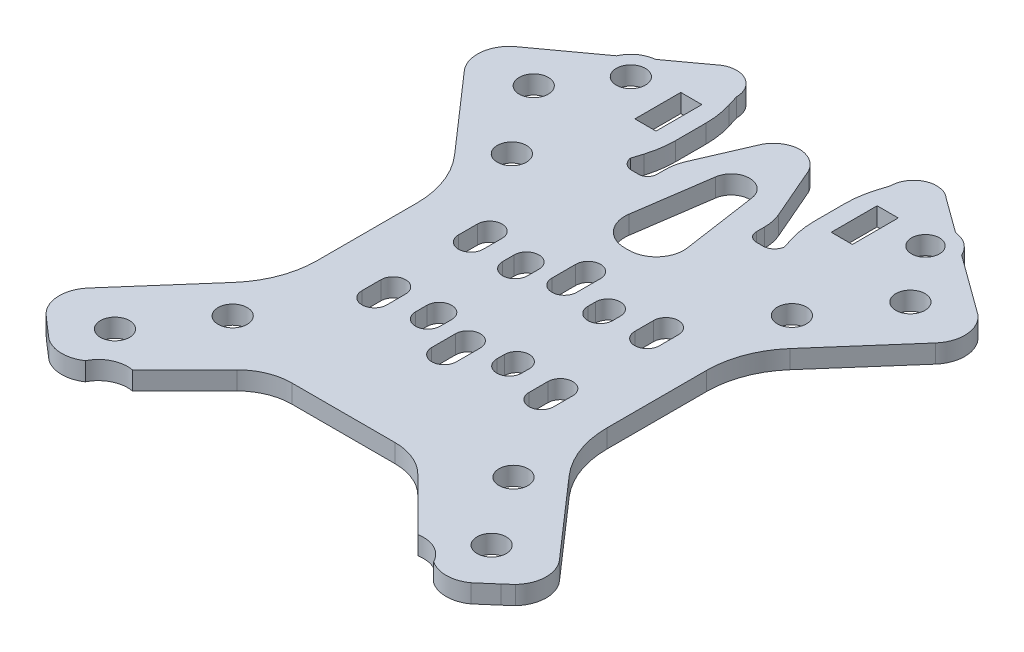
SolidWorks part; units mm, degrees
ref_plane "Alzado" through (0, 0, 0) normal (0, 0, 1) x (1, 0, 0)
ref_plane "Planta" through (0, 0, 0) normal (0, 1, 0) x (1, 0, 0)
ref_plane "Vista lateral" through (0, 0, 0) normal (1, 0, 0) x (0, 0, -1)
sketch "Croquis2" plane through (0, 0, 0) normal (0, 1, 0) x (1, 0, 0)
  line L0 (0, -1035.6845) -> (0, -17.8422) construction
  line L5 (0.7327, 0.4652) -> (1.362, 0.4652) construction
  line L7 (-18.2554, -12.0161) -> (-25.6541, -20.4709)
  line L14 (-15.7808, 5.4307) -> (-15.7808, -5.4307)
  line L18 (0, -8.7278) -> (0, 9.8136) construction
  line L20 (-24.7424, -25.9141) -> (-22.9722, -27.4461)
  line L25 (15.4321, 26.7753) -> (15.4536, 26.7998)
  line L29 (0, 8.3081) -> (0, 5.7183) construction
  line L30 (-18.2554, 12.0161) -> (-25.6541, 20.4709)
  line L31 (-24.7424, -25.9141) -> (-25.5735, -25.1696)
  line L45 (-1.35, 8.3081) -> (-1.35, 5.7183)
  line L53 (-9.1589, -5.8146) -> (-9.1589, -3.7612) construction
  line L54 (-7.8089, -5.8146) -> (-7.8089, -3.7612)
  line L55 (-10.5089, -5.8146) -> (-10.5089, -3.7612)
  line L58 (-4.2409, -4.9118) -> (-4.2409, -3.6663) construction
  line L59 (-2.8909, -4.9118) -> (-2.8909, -3.6663)
  line L60 (-5.5909, -4.9118) -> (-5.5909, -3.6663)
  line L61 (1.35, 8.3081) -> (1.35, 5.7183)
  line L64 (4.6229, 5.8422) -> (4.6229, 5.0048) construction
  line L67 (9.5409, -6.317) -> (9.5409, -4.2636) construction
  line L68 (8.1909, -6.317) -> (8.1909, -4.2636)
  line L69 (10.8909, -6.317) -> (10.8909, -4.2636)
  line L70 (4.6229, -4.9118) -> (4.6229, -4.0745) construction
  line L71 (3.2729, -4.9118) -> (3.2729, -4.0745)
  line L72 (5.9729, -4.9118) -> (5.9729, -4.0745)
  line L74 (-11.8441, 30.2416) -> (-9.5441, 30.2416)
  line L81 (-15.5416, -25.7927) -> (-9.8561, -20.0974)
  line L82 (5.6203, -18.3469) -> (-5.6203, -18.3469)
  line L94 (0, -7.3778) -> (0, -4.7879) construction
  line L95 (-1.35, -7.3778) -> (-1.35, -4.7879)
  line L96 (1.35, -7.3778) -> (1.35, -4.7879)
  line L103 (0.2351, 12.5224) -> (-0.2351, 12.5224)
  line L104 (-3.1825, 15.9307) -> (-1.9791, 24.1856)
  line L105 (3.1825, 15.9307) -> (1.9791, 24.1856)
  line L107 (5.0007, 24.0657) -> (2.5182, 29.8007)
  line L113 (8.3962, 23.8714) -> (8.3962, 23.8712)
  line L114 (15.5416, -25.7927) -> (9.8561, -20.0974)
  line L115 (24.7424, -25.9141) -> (22.9722, -27.4461)
  line L116 (-25.3551, 25.4165) -> (-18.7889, 30.2002)
  line L117 (18.2554, 12.0161) -> (25.6541, 20.4709)
  line L118 (-16.3426, 31.9825) -> (-12.5615, 34.7372)
  line L119 (16.3426, 31.9825) -> (12.5615, 34.7372)
  line L120 (25.3551, 25.4165) -> (18.7889, 30.2002)
  line L121 (15.7808, 5.4307) -> (15.7808, -5.4307)
  line L122 (18.2554, -12.0161) -> (25.6541, -20.4709)
  line L123 (24.7424, -25.9141) -> (25.5735, -25.1696)
  line L124 (7.1462, 20.2186) -> (6.4122, 20.2186)
  line L125 (5.4122, 21.2186) -> (5.4122, 22.0794)
  line L126 (-5.4122, 21.2186) -> (-5.4122, 22.0794)
  line L127 (-7.1462, 20.2186) -> (-6.4122, 20.2186)
  line L130 (-5.0007, 24.0657) -> (-2.5182, 29.8007)
  line L135 (-9.5441, 30.2416) -> (-9.5441, 25.2416)
  line L136 (-9.5441, 25.2416) -> (-11.8441, 25.2416)
  line L137 (-11.8441, 25.2416) -> (-11.8441, 30.2416)
  line L142 (11.8441, 25.2416) -> (11.8441, 30.2416)
  line L143 (9.5441, 25.2416) -> (11.8441, 25.2416)
  line L144 (9.5441, 30.2416) -> (9.5441, 25.2416)
  line L145 (11.8441, 30.2416) -> (9.5441, 30.2416)
  line L146 (-7.5808, 25.3984) -> (-7.5808, 28.7216)
  line L147 (-8.0214, 31.6573) -> (-8.3949, 32.8733)
  line L148 (-8.0365, 22.4142) -> (-8.3848, 21.3001)
  line L149 (8.0365, 22.4142) -> (8.3848, 21.3001)
  line L150 (7.5808, 25.3984) -> (7.5808, 28.7216)
  line L151 (8.0214, 31.6573) -> (8.3949, 32.8733)
  line L152 (3.2729, 5.8422) -> (3.2729, 5.0048)
  line L153 (5.9729, 5.8422) -> (5.9729, 5.0048)
  line L154 (9.5409, 7.2474) -> (9.5409, 5.194) construction
  line L155 (8.1909, 7.2474) -> (8.1909, 5.194)
  line L156 (10.8909, 7.2474) -> (10.8909, 5.194)
  line L157 (-4.2409, 5.8422) -> (-4.2409, 4.5967) construction
  line L158 (-2.8909, 5.8422) -> (-2.8909, 4.5967)
  line L159 (-5.5909, 5.8422) -> (-5.5909, 4.5967)
  line L160 (-9.1589, 6.745) -> (-9.1589, 4.6916) construction
  line L161 (-7.8089, 6.745) -> (-7.8089, 4.6916)
  line L162 (-10.5089, 6.745) -> (-10.5089, 4.6916)
  circle A13 centre (-15.25, 15.25) radius 1.59
  arc A20 (-25.5735, -25.1696) -> (-25.6541, -20.4709) centre (-23.0202, -22.7758) cw
  arc A25 (-25.3551, 25.4165) -> (-25.6541, 20.4709) centre (-23.0367, 22.7945) ccw
  circle A27 centre (-20.4756, 22.858) radius 1.5875
  arc A43 (-7.8089, -5.8146) -> (-10.5089, -5.8146) centre (-9.1589, -5.8146) cw
  arc A44 (-10.5089, -3.7612) -> (-7.8089, -3.7612) centre (-9.1589, -3.7612) cw
  arc A47 (-2.8909, -4.9118) -> (-5.5909, -4.9118) centre (-4.2409, -4.9118) cw
  arc A48 (-5.5909, -3.6663) -> (-2.8909, -3.6663) centre (-4.2409, -3.6663) cw
  arc A53 (8.1909, -6.317) -> (10.8909, -6.317) centre (9.5409, -6.317) ccw
  arc A54 (10.8909, -4.2636) -> (8.1909, -4.2636) centre (9.5409, -4.2636) ccw
  arc A55 (3.2729, -4.9118) -> (5.9729, -4.9118) centre (4.6229, -4.9118) ccw
  arc A56 (5.9729, -4.0745) -> (3.2729, -4.0745) centre (4.6229, -4.0745) ccw
  arc A61 (-12.5615, 34.7372) -> (-8.3949, 32.8733) centre (-10.8949, 32.8737) cw
  arc A62 (12.5615, 34.7372) -> (8.3949, 32.8733) centre (10.8949, 32.8737) ccw
  arc A69 (-1.35, -7.3778) -> (1.35, -7.3778) centre (0, -7.3778) ccw
  arc A70 (1.35, -4.7879) -> (-1.35, -4.7879) centre (0, -4.7879) ccw
  arc A73 (-2.5182, 29.8007) -> (0, 31.3573) centre (0.1129, 28.3594) cw
  arc A74 (-0.2351, 12.5224) -> (-3.1825, 15.9307) centre (-0.2351, 15.501) cw
  arc A75 (0.2351, 12.5224) -> (3.1825, 15.9307) centre (0.2351, 15.501) ccw
  arc A76 (-1.9791, 24.1856) -> (1.9791, 24.1856) centre (0, 23.8971) cw
  arc A77 (8.3962, 23.8712) -> (8.3962, 23.8714) centre (0.6284, 23.8713) ccw
  arc A78 (2.5182, 29.8007) -> (0, 31.3573) centre (-0.1129, 28.3594) ccw
  arc A81 (-18.2554, 12.0161) -> (-15.7808, 5.4307) centre (-25.7808, 5.4307) cw
  arc A82 (-15.7808, -5.4307) -> (-18.2554, -12.0161) centre (-25.7808, -5.4307) cw
  circle A85 centre (-20.4756, 22.858) radius 1.5875 construction
  circle A89 centre (-16.0404, 28.9977) radius 1.5875
  arc A93 (-5.6203, -18.3469) -> (-9.8561, -20.0974) centre (-5.6203, -24.3469) ccw
  arc A96 (5.6203, -18.3469) -> (9.8561, -20.0974) centre (5.6203, -24.3469) cw
  arc A97 (-22.9722, -27.4461) -> (-18.9648, -27.4884) centre (-20.9382, -24.5978) ccw
  arc A98 (22.9722, -27.4461) -> (18.9648, -27.4884) centre (20.9382, -24.5978) cw
  arc A99 (-16.3426, 31.9825) -> (-18.7889, 30.2002) centre (-16.0404, 28.9977) ccw
  arc A100 (16.3426, 31.9825) -> (18.7889, 30.2002) centre (16.0404, 28.9977) cw
  arc A101 (25.3551, 25.4165) -> (25.6541, 20.4709) centre (23.0367, 22.7945) cw
  arc A102 (18.2554, 12.0161) -> (15.7808, 5.4307) centre (25.7808, 5.4307) ccw
  arc A103 (15.7808, -5.4307) -> (18.2554, -12.0161) centre (25.7808, -5.4307) ccw
  arc A104 (25.5735, -25.1696) -> (25.6541, -20.4709) centre (23.0202, -22.7758) ccw
  arc A105 (7.1462, 20.2186) -> (8.3848, 21.3001) centre (7.1462, 21.4686) ccw
  circle A108 centre (15.25, 15.25) radius 1.59
  arc A112 (18.9648, -27.4884) -> (15.5416, -25.7927) centre (16.13, -28.9079) ccw
  arc A113 (-18.9648, -27.4884) -> (-15.5416, -25.7927) centre (-16.13, -28.9079) cw
  arc A114 (6.4122, 20.2186) -> (5.4122, 21.2186) centre (6.4122, 21.2186) cw
  arc A115 (5.0007, 24.0657) -> (5.4122, 22.0794) centre (0.4122, 22.0794) cw
  arc A116 (-5.0007, 24.0657) -> (-5.4122, 22.0794) centre (-0.4122, 22.0794) ccw
  arc A117 (-6.4122, 20.2186) -> (-5.4122, 21.2186) centre (-6.4122, 21.2186) ccw
  arc A118 (-7.1462, 20.2186) -> (-8.3848, 21.3001) centre (-7.1462, 21.4686) cw
  arc A119 (-1.35, 8.3081) -> (1.35, 8.3081) centre (0, 8.3081) cw
  arc A120 (-7.5808, 28.7216) -> (-8.0214, 31.6573) centre (-17.5808, 28.7216) ccw
  arc A121 (-8.0365, 22.4142) -> (-7.5808, 25.3984) centre (-17.5808, 25.3984) ccw
  arc A122 (8.0365, 22.4142) -> (7.5808, 25.3984) centre (17.5808, 25.3984) cw
  arc A123 (7.5808, 28.7216) -> (8.0214, 31.6573) centre (17.5808, 28.7216) cw
  arc A124 (1.35, 5.7183) -> (-1.35, 5.7183) centre (0, 5.7183) cw
  arc A125 (3.2729, 5.8422) -> (5.9729, 5.8422) centre (4.6229, 5.8422) cw
  arc A126 (5.9729, 5.0048) -> (3.2729, 5.0048) centre (4.6229, 5.0048) cw
  arc A127 (8.1909, 7.2474) -> (10.8909, 7.2474) centre (9.5409, 7.2474) cw
  arc A128 (10.8909, 5.194) -> (8.1909, 5.194) centre (9.5409, 5.194) cw
  arc A129 (-2.8909, 5.8422) -> (-5.5909, 5.8422) centre (-4.2409, 5.8422) ccw
  arc A130 (-5.5909, 4.5967) -> (-2.8909, 4.5967) centre (-4.2409, 4.5967) ccw
  arc A131 (-7.8089, 6.745) -> (-10.5089, 6.745) centre (-9.1589, 6.745) ccw
  arc A132 (-10.5089, 4.6916) -> (-7.8089, 4.6916) centre (-9.1589, 4.6916) ccw
  circle A133 centre (20.5651, -22.7681) radius 1.5875
  circle A134 centre (-20.341, -22.8884) radius 1.5875
  circle A135 centre (-15.1603, -15.2499) radius 1.59
  circle A137 centre (15.3396, -15.1602) radius 1.5875
  circle A138 centre (20.4306, 22.9783) radius 1.5875
  circle A139 centre (15.9594, 29.0918) radius 1.52
  point P22 (-19.2386, -30.7543)
  point P25 (-27.9717, -23.1193)
  point P34 (27.9352, -23.1152)
  point P35 (19.2057, -30.7543)
  point P50 (0, 7.0132)
  point P53 (19.2057, 30.7543)
  point P54 (-27.9681, 23.1152)
  point P55 (-19.2386, 30.7543)
  point P78 (9.0366, 19.1852)
  point P88 (-9.0366, 19.1852)
  point P99 (-9.1589, -4.7879)
  point P105 (4.6229, 5.4235)
  point P117 (-4.2409, -4.2891)
  point P122 (9.5409, 6.2207)
  point P129 (-4.2409, 5.2194)
  point P138 (9.5409, -5.2903)
  point P145 (4.6229, -4.4932)
  point P152 (0, 10.5431)
  point P154 (7.2034, 12.404)
  point P155 (-9.1589, 5.7183)
  point P157 (-7.2034, 12.404)
  point P162 (0, -18.3469)
  point P169 (16.3904, 27.8718)
  point P179 (0, -6.0829)
  point P192 (-21.5646, 28.6744)
  point P197 (-1.6643, 31.3594)
  point P200 (0, 12.8836)
  point P203 (8.2335, 13.1366)
  point P209 (-8.2335, 13.1366)
  point P217 (15.7479, 9.1883)
  point P220 (15.7479, -9.1883)
  point P223 (-15.7808, 9.1883)
  point P226 (-15.7808, -9.1883)
  point P232 (0, 12.5224)
  dimension "D3" = 6
  dimension "D5" = 3.18
  dimension "D2" = 6
  dimension "D9" = 3
  dimension "D7" = 3.175
  dimension "D10" = 2.7
  dimension "D12" = 5
  dimension "D13" = 2
  dimension "D14" = 10
  dimension "D19" = 2.5
  dimension "D8" = 1
  dimension "D6" = 1.25
  dimension "D15" = 1.35
  dimension "D18" = 3.175
  dimension "D4" = 15.25
  dimension "D11" = 2.7
  dimension "D16" = 2.7
  dimension "D17" = 2.7
sketch "Croquis3" plane through (0, 0, 0) normal (0, 1, 0) x (1, 0, 0)
  line L0 (0, 0) -> (0, 33.3632) construction
extrude "Saliente-Extruir1" add sketch "Croquis2" along normal blind 2
